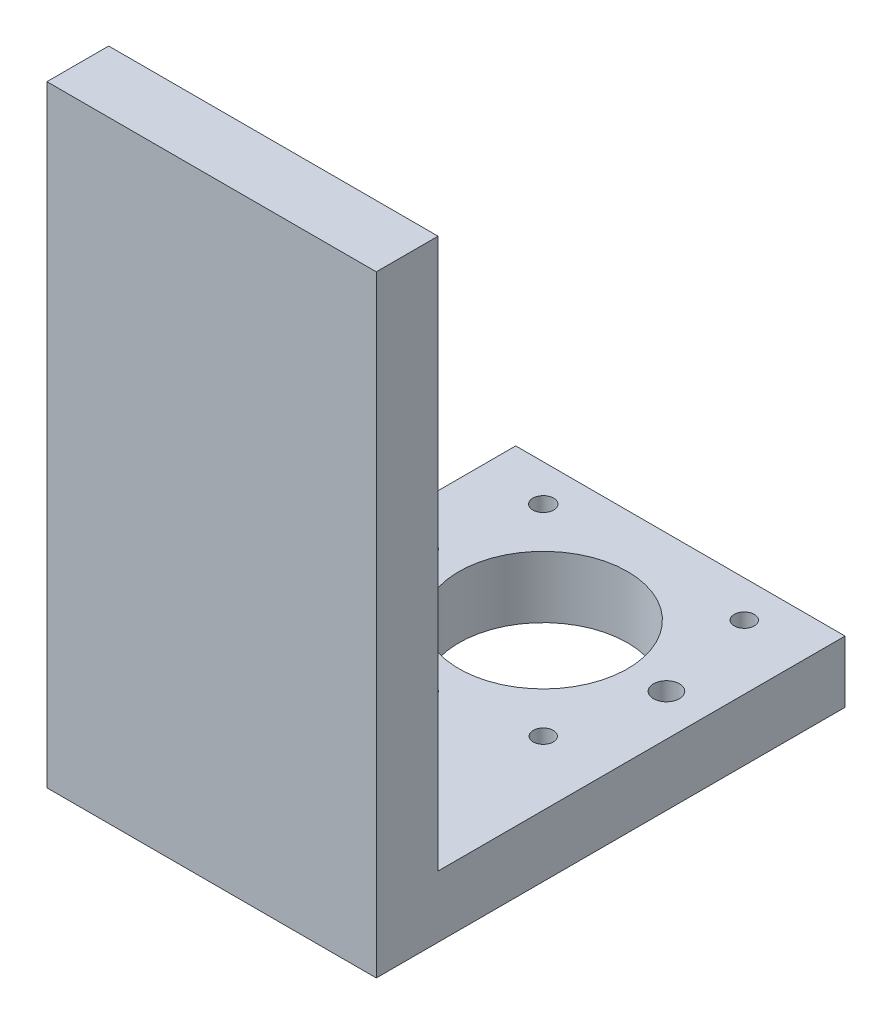
SolidWorks part; units mm, degrees
ref_plane "Alzado" through (0, 0, 0) normal (0, 0, 1) x (1, 0, 0)
ref_plane "Planta" through (0, 0, 0) normal (0, 1, 0) x (1, 0, 0)
ref_plane "Vista lateral" through (0, 0, 0) normal (1, 0, 0) x (0, 0, -1)
sketch "Croquis1" plane through (0, 0, 0) normal (0, 1, 0) x (1, 0, 0)
  line L1 (-25.4, 42.5) -> (25.4, 42.5)
  line L2 (-25.4, 42.5) -> (-25.4, -42.5)
  line L3 (-25.4, -42.5) -> (25.4, -42.5)
  line L4 (25.4, 42.5) -> (25.4, -42.5)
  line L5 (-25.4, 42.5) -> (25.4, -42.5) construction
  line L6 (-25.4, -42.5) -> (25.4, 42.5) construction
  point P0 (0, 0)
  dimension "D1" = 85
  dimension "D2" = 50.8
extrude "Saliente-Extruir1" add sketch "Croquis1" along normal blind 9.525
sketch "Croquis2" plane through (0, 0, 0) normal (0, -1, 0) x (1, 0, 0)
  circle A0 centre (0, -21.35) radius 13
extrude "Cortar-Extruir1" cut sketch "Croquis2" against normal through all
sketch "Croquis3" plane through (0, 0, 0) normal (0, -1, 0) x (1, 0, 0)
  circle A0 centre (-15.5, -5.85) radius 1.55
  circle A1 centre (15.5, -5.85) radius 1.55
  circle A2 centre (15.5, -36.85) radius 1.55
  circle A3 centre (-15.5, -36.85) radius 1.6
extrude "Cortar-Extruir2" cut sketch "Croquis3" against normal through all
sketch "Croquis4" plane through (0, 9.525, 0) normal (0, 1, 0) x (1, 0, 0)
  line L0 (-13, 21.35) -> (13, 21.35) construction
  circle A0 centre (-19, 21.35) radius 2
  circle A1 centre (19, 21.35) radius 2
  circle A2 centre (0, 2.35) radius 2
  circle A3 centre (0, 21.35) radius 13 construction
  point P10 (0, 0)
  point P14 (0, 0)
  point P15 (0, 21.35)
  dimension "D3" = 4
  dimension "D5" = 4
  dimension "D4" = 4
  dimension "D1" = 38
  dimension "D2" = 19
  dimension "D6" = 19
extrude "Cortar-Extruir3" cut sketch "Croquis4" against normal through all
sketch "Croquis5" plane through (0, 9.525, 0) normal (0, 1, 0) x (1, 0, 0)
  line L0 (25.4, -42.5) -> (25.4, 42.5) construction
  line L1 (-25.4, -42.5) -> (25.4, -42.5)
  line L2 (-25.4, -42.5) -> (-25.4, -29.8)
  line L3 (-25.4, -29.8) -> (25.4, -29.8)
  line L4 (25.4, -42.5) -> (25.4, -29.8)
  dimension "D1" = 12.7
extrude "Cortar-Extruir4" cut sketch "Croquis5" against normal through all
sketch "Croquis6" plane through (0, 9.525, 0) normal (0, 1, 0) x (1, 0, 0)
  line L0 (25.4, -29.8) -> (25.4, 42.5) construction
  line L1 (-25.4, -29.8) -> (25.4, -29.8)
  line L2 (-25.4, -29.8) -> (-25.4, -20.275)
  line L3 (-25.4, -20.275) -> (25.4, -20.275)
  line L4 (25.4, -29.8) -> (25.4, -20.275)
  dimension "D1" = 9.525
extrude "Saliente-Extruir2" add sketch "Croquis6" along normal blind 84.8
equation "\"D2@Croquis4\"=\"D1@Croquis4\"/2"
equation "\"D5@Croquis4\"=\"D3@Croquis4\""
equation "\"D6@Croquis4\"=\"D2@Croquis4\""
equation "\"D4@Croquis4\"=\"D3@Croquis4\""
